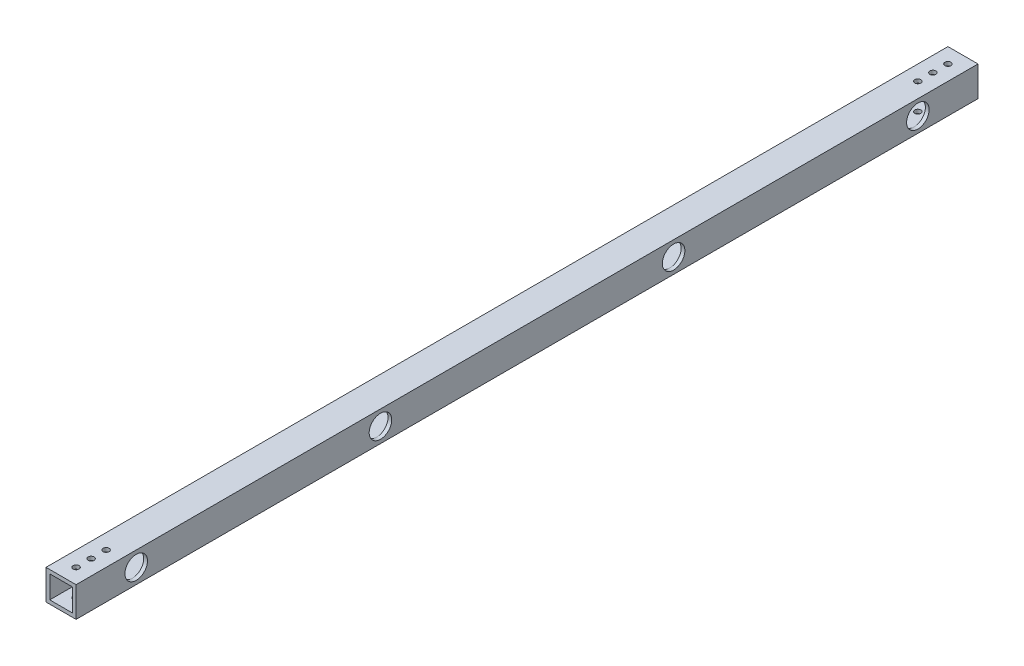
SolidWorks part; units mm, degrees
material "6061 Alloy"
ref_plane "Front" through (0, 0, 0) normal (0, 0, 1) x (1, 0, 0)
ref_plane "Top" through (0, 0, 0) normal (0, 1, 0) x (1, 0, 0)
ref_plane "Right" through (0, 0, 0) normal (1, 0, 0) x (0, 0, -1)
sketch "Sketch1" plane through (0, 0, 0) normal (0, 0, 1) x (1, 0, 0)
  line L1 (0, 0) -> (-25.4, 0)
  line L2 (0, 0) -> (0, 25.4)
  line L3 (0, 25.4) -> (-25.4, 25.4)
  line L4 (-25.4, 0) -> (-25.4, 25.4)
  line L5 (-22.225, 22.225) -> (-3.175, 22.225)
  line L6 (-22.225, 22.225) -> (-22.225, 3.175)
  line L7 (-22.225, 3.175) -> (-3.175, 3.175)
  line L8 (-3.175, 22.225) -> (-3.175, 3.175)
  dimension "D1" = 3.175
  dimension "D2" = 3.175
  dimension "D3" = 3.175
  dimension "D4" = 3.175
  dimension "D5" = 25.4
extrude "Boss-Extrude1" add sketch "Sketch1" along normal blind 762
hole_wizard "#10 Clearance Hole1" positions "Sketch3" profile "Sketch4" hole size "#10" standard "ANSI Inch"
sketch "Sketch3" plane through (0, 25.4, 0) normal (0, 1, 0) x (1, 0, 0)
  line L0 (0, -762) -> (-25.4, -762) construction
  line L1 (0, -762) -> (0, 0) construction
  line L2 (0, 0) -> (-25.4, 0) construction
  point P0 (-12.7, -749.3)
  point P2 (-12.7, -736.6)
  point P4 (-12.7, -723.9)
  point P7 (-12.7, -38.1)
  point P9 (-12.7, -25.4)
  point P11 (-12.7, -12.7)
  dimension "D1" = 12.7
  dimension "D2" = 12.7
  dimension "D3" = 12.7
  dimension "D4" = 12.7
  dimension "D5" = 12.7
  dimension "D6" = 12.7
  dimension "D7" = 12.7
sketch "Sketch4" plane through (-12.7, 25.4, 749.3) normal (1, 0, 0) x (0, 0, 1)
  line L0 (0, 0) -> (0, 26.9328)
  line L1 (0, 26.9328) -> (2.5527, 25.399)
  line L2 (2.5527, 25.399) -> (2.5527, 0)
  line L5 (2.5527, 0) -> (0, 0)
  line L10 (0, 26.9328) -> (-2.5527, 25.399) construction
  line L11 (0, -6.35) -> (0, 107.95) construction
  dimension "Hole Dia." = 5.1054
  dimension "Hole Depth" = 25.399
  dimension "Drill Angle" = 118
sketch "Sketch5" plane through (-25.4, 0, 0) normal (-1, 0, 0) x (0, 0, 1)
  line L1 (762, 0) -> (0, 0) construction
  line L2 (0, 25.4) -> (0, 0) construction
  line L3 (762, 25.4) -> (762, 0) construction
  circle A0 centre (50.8, 12.7) radius 9.525
  circle A1 centre (711.2, 12.7) radius 9.525
  circle A2 centre (504.825, 12.7) radius 9.525
  circle A3 centre (257.175, 12.7) radius 9.525
  dimension "D4" = 19.05
  dimension "D3" = 50.8
  dimension "D5" = 50.8
  dimension "D6" = 12.7
  dimension "D1" = 257.175
  dimension "D2" = 257.175
extrude "Cut-Extrude1" cut sketch "Sketch5" against normal up to surface (25.4 mm away) up to face at (0, 12.7, 381)
equation "\"D2@Sketch1\"=\"D1@Sketch1\""
equation "\"D3@Sketch1\"=\"D2@Sketch1\""
equation "\"D2@Sketch5\"=\"D1@Sketch5\""
